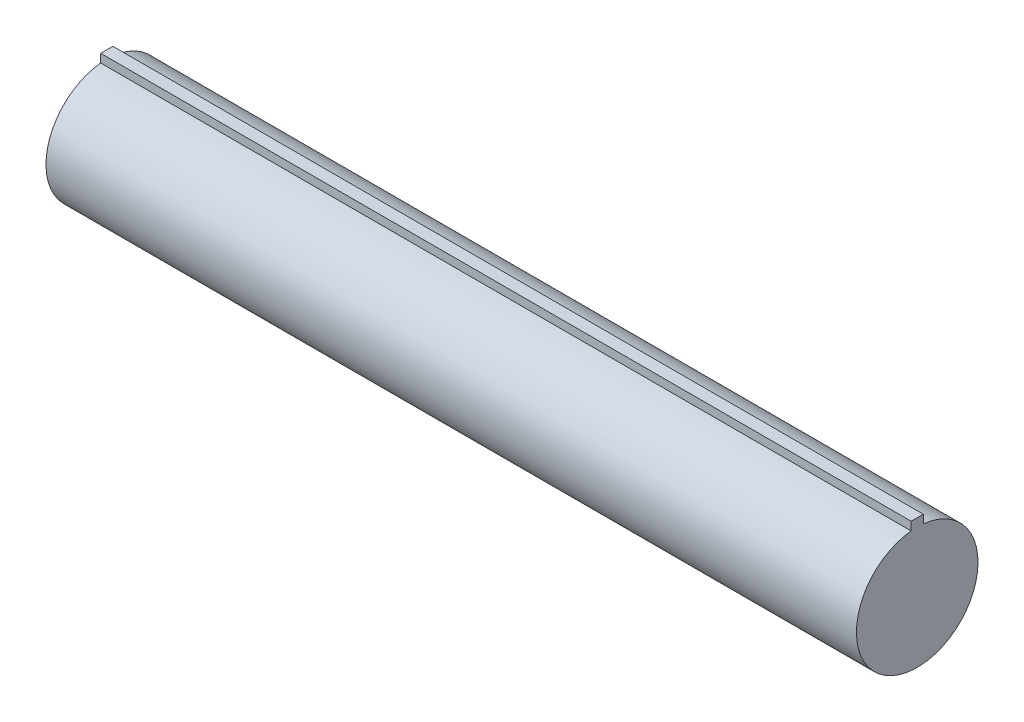
SolidWorks part; units mm, degrees
ref_plane "前视基准面" through (0, 0, 0) normal (0, 0, 1) x (1, 0, 0)
ref_plane "上视基准面" through (0, 0, 0) normal (0, 1, 0) x (1, 0, 0)
ref_plane "右视基准面" through (0, 0, 0) normal (1, 0, 0) x (0, 0, -1)
other "Configuration Table"
sketch "草图1" plane through (0, 0, 0) normal (1, 0, 0) x (0, 0, -1)
  line L1 (-1.5, 0) -> (1.5, 0)
  line L2 (-1.5, 0) -> (-1.5, 17)
  line L3 (-1.5, 17) -> (1.5, 17)
  line L4 (1.5, 0) -> (1.5, 17)
  circle A0 centre (0, 0) radius 15
  point P7 (0, 0)
  dimension "D1" = 30
  dimension "D2" = 3
  dimension "D3" = 17
extrude "凸台-拉伸1" add sketch "草图1" along normal mid plane 200 contours L2 A0 L4 L1 | A0 L4 L3 L2 | L4 A0 L2 L1
